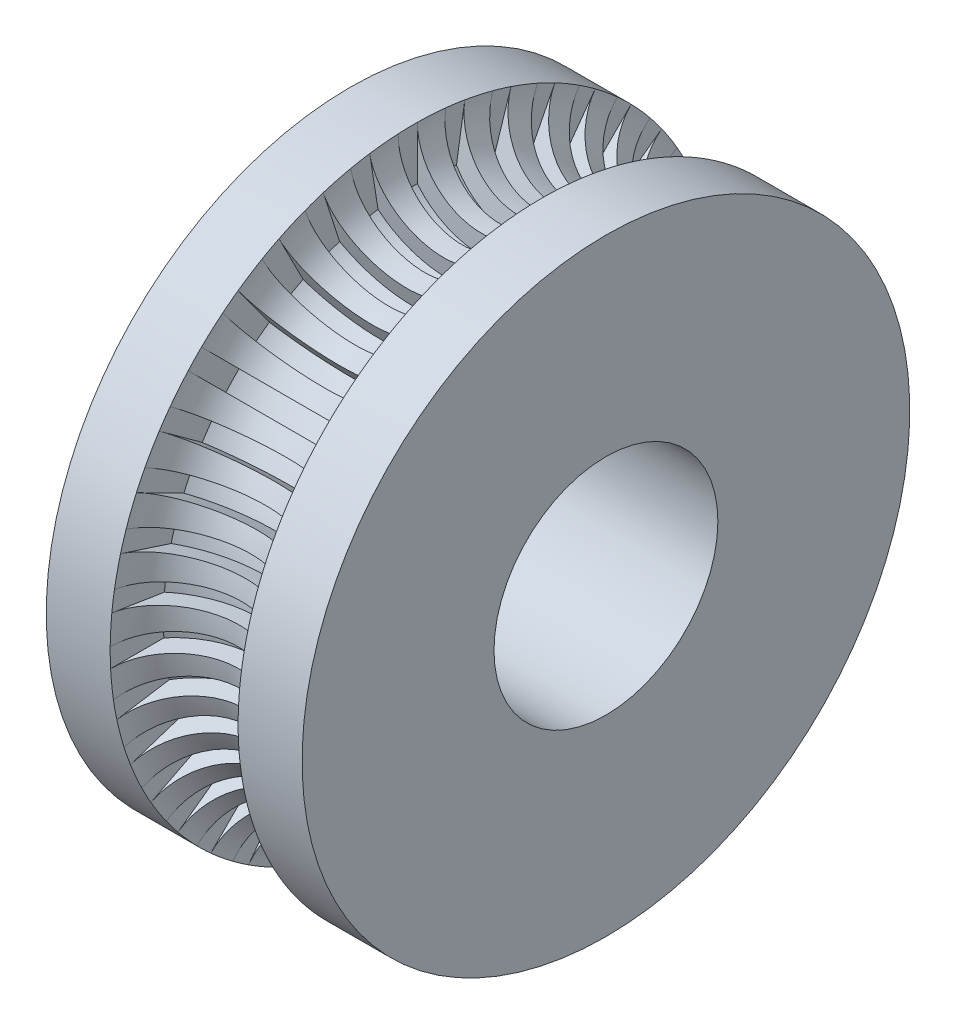
SolidWorks part; units mm, degrees
ref_plane "Front Plane" through (0, 0, 0) normal (0, 0, 1) x (1, 0, 0)
ref_plane "Top Plane" through (0, 0, 0) normal (0, 1, 0) x (1, 0, 0)
ref_plane "Right Plane" through (0, 0, 0) normal (1, 0, 0) x (0, 0, -1)
sketch "Sketch1" plane through (0, 0, 0) normal (0, 0, 1) x (1, 0, 0)
  line L0 (0, 0) -> (0, 4.75)
  line L1 (0, 4.75) -> (1, 4.75)
  line L2 (3, 4.75) -> (4, 4.75)
  line L3 (4, 4.75) -> (4, 0)
  line L4 (4, 0) -> (0, 0)
  line L5 (2, 3.75) -> (2, 0) construction
  arc A0 (1, 4.75) -> (3, 4.75) centre (2, 4.75) ccw
  dimension "D1" = 1
  dimension "D2" = 1
  dimension "D3" = 1
  dimension "D4" = 3.75
revolve "Revolve1" add sketch "Sketch1" angle 360 about L4
sketch "Sketch3" plane through (0, 0, 0) normal (-1, 0, 0) x (0, 0, 1)
  circle A0 centre (0, 0) radius 1.75
  dimension "D1" = 3.5
extrude "Cut-Extrude1" cut sketch "Sketch3" against normal up to surface (4 mm away) up to face at (4, 4.75, 0)
ref_plane "Plane1" through (2, 0, 0) normal (1, 0, 0) x (0, 0, -1)
ref_plane "Plane2" through (0, 0, 4.75) normal (0, 0, 1) x (1, 0, 0)
sketch "Sketch5" plane through (0, 0, 4.75) normal (0, 0, 1) x (1, 0, 0)
  line L0 (1, 4.75) -> (1, -4.75) construction
  line L1 (1, 0.0508) -> (3, 0.0508)
  line L2 (1, 0.0508) -> (1, -0.2492)
  line L3 (1, -0.2492) -> (3, -0.2492)
  line L4 (3, 0.0508) -> (3, -0.2492)
  line L5 (3, 4.75) -> (3, -4.75) construction
  dimension "D1" = 0.3
extrude "Cut-Extrude2" cut sketch "Sketch5" against normal offset from surface (0.831 mm away) 0.3
pattern_circular "CirPattern1" count 40 over 360 about axis through (0, 0, 0) along (1, 0, 0) of "Cut-Extrude2"
equation "\"D3@Sketch1\"=\"D2@Sketch1\""
